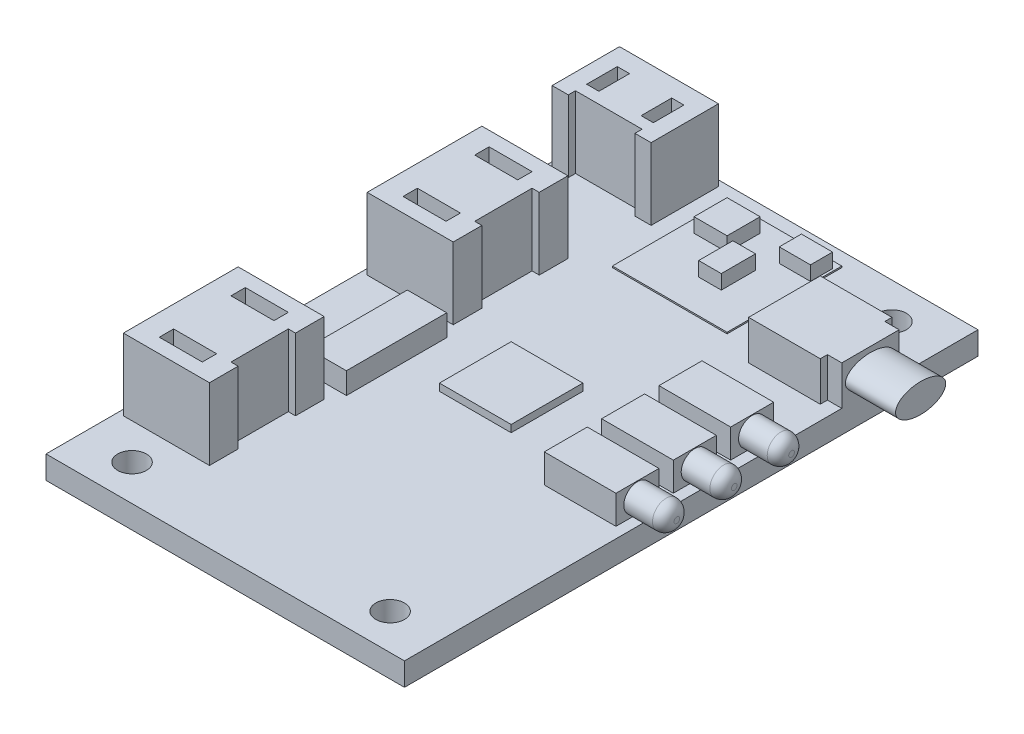
SolidWorks part; units mm, degrees
ref_plane "Front Plane" through (0, 0, 0) normal (0, 0, 1) x (1, 0, 0)
ref_plane "Top Plane" through (0, 0, 0) normal (0, 1, 0) x (1, 0, 0)
ref_plane "Right Plane" through (0, 0, 0) normal (1, 0, 0) x (0, 0, -1)
sketch "Sketch1" plane through (0, 0, 0) normal (0, 1, 0) x (1, 0, 0)
  line L1 (0, 0) -> (25, 0)
  line L2 (0, 0) -> (0, 40)
  line L3 (0, 40) -> (25, 40)
  line L4 (25, 0) -> (25, 40)
  dimension "D1" = 40
  dimension "D2" = 25
extrude "Boss-Extrude1" add sketch "Sketch1" along normal blind 1.6 contours L2 L3 L4 L1
sketch "Sketch2" plane through (0, 1.6, 0) normal (0, 1, 0) x (1, 0, 0)
  line L1 (14.9411, 22.5) -> (9.9411, 22.5)
  line L2 (14.9411, 22.5) -> (14.9411, 17.5)
  line L3 (14.9411, 17.5) -> (9.9411, 17.5)
  line L4 (9.9411, 22.5) -> (9.9411, 17.5)
  line L5 (14.9411, 22.5) -> (9.9411, 17.5) construction
  line L6 (14.9411, 17.5) -> (9.9411, 22.5) construction
  point P0 (12.4411, 20)
  point P5 (12.5, 19.8855)
  point P6 (12.4411, 20.1289)
  dimension "D1" = 5
  dimension "D2" = 20
extrude "Boss-Extrude2" add sketch "Sketch2" along normal blind 0.5
sketch "Sketch3" plane through (0, 1.6, 0) normal (0, 1, 0) x (1, 0, 0)
  line L0 (0, 0) -> (25, 0) construction
  line L1 (19.25, 18.5) -> (24.25, 18.5)
  line L2 (19.25, 18.5) -> (19.25, 15.5)
  line L3 (19.25, 15.5) -> (24.25, 15.5)
  line L4 (24.25, 18.5) -> (24.25, 15.5)
  line L5 (19.25, 18.5) -> (24.25, 15.5) construction
  line L6 (19.25, 15.5) -> (24.25, 18.5) construction
  line L7 (25, 0) -> (25, 40) construction
  point P0 (21.75, 17)
  point P5 (21.4832, 17.3272)
  dimension "D1" = 15.5
  dimension "D2" = 3
  dimension "D3" = 5
  dimension "D4" = 0.75
extrude "Boss-Extrude3" add sketch "Sketch3" along normal blind 2
sketch "Sketch4" plane through (24.25, 0, 0) normal (1, 0, 0) x (0, 0, -1)
  line L6 (18.5, 3.6) -> (18.5, 1.6) construction
  line L8 (15.5, 3.6) -> (18.5, 3.6) construction
  circle A0 centre (17, 2.6) radius 0.95
  point P2 (0, 0)
  point P7 (18.5, 2.6)
  point P10 (17, 3.6)
  dimension "D1" = 1.9
extrude "Boss-Extrude6" add sketch "Sketch4" along normal blind 2.75
fillet "Fillet2" radius 0.75 1 edges at (27, 2.6, -17.95)
pattern_linear "LPattern2" count 3 spacing 4 along (0, 0, -1) of "Boss-Extrude3", "Boss-Extrude6", "Fillet2"
sketch "Sketch5" plane through (0, 1.6, 0) normal (0, 1, 0) x (1, 0, 0)
  line L0 (24, 30.5) -> (24, 30)
  line L1 (24, 35) -> (19, 35)
  line L2 (24, 35) -> (24, 34.5)
  line L3 (24, 30) -> (19, 30)
  line L4 (19, 35) -> (19, 30)
  line L5 (24, 35) -> (19, 30) construction
  line L6 (24, 30) -> (19, 35) construction
  line L7 (25, 0) -> (25, 40) construction
  line L8 (0, 40) -> (25, 40) construction
  line L9 (25, 34.5) -> (24, 34.5)
  line L14 (25, 34.5) -> (25, 30.5)
  line L15 (25, 30.5) -> (24, 30.5)
  point P0 (21.5, 32.5)
  point P9 (21.5, 32.5)
  point P14 (25, 32.5)
  dimension "D1" = 1
  dimension "D2" = 5
  dimension "D3" = 5
  dimension "D4" = 4
extrude "Boss-Extrude7" add sketch "Sketch5" along normal blind 2.75
sketch "Sketch6" plane through (25, 0, 0) normal (1, 0, 0) x (0, 0, -1)
  line L0 (30.5, 4.35) -> (34.5, 4.35) construction
  line L1 (35, 4.35) -> (35, 1.6) construction
  ellipse E0 centre (32.5, 2.975) end of major axis (30.75, 2.975) minor radius 1
  point P1 (0, 0)
  point P2 (34.1034, 2.9375)
  point P5 (32.5, 4.35)
  point P13 (35, 2.975)
  point P14 (0, 0)
  point P15 (32.5, 2.2386)
  dimension "D1" = 3.5
  dimension "D2" = 2
extrude "Boss-Extrude8" add sketch "Sketch6" along normal blind 3.5
sketch "Sketch7" plane through (0, 1.6, 0) normal (0, 1, 0) x (1, 0, 0)
  line L0 (0, 40) -> (25, 40) construction
  line L1 (16.5, 39) -> (8.5, 39)
  line L2 (16.5, 39) -> (16.5, 31)
  line L3 (16.5, 31) -> (8.5, 31)
  line L4 (8.5, 39) -> (8.5, 31)
  line L5 (16.5, 39) -> (8.5, 31) construction
  line L6 (16.5, 31) -> (8.5, 39) construction
  line L8 (16.3371, 38.5219) -> (14.1621, 38.5219)
  line L9 (16.3371, 38.5219) -> (16.3371, 36.9773)
  line L10 (16.3371, 36.9773) -> (14.1621, 36.9773)
  line L11 (14.1621, 38.5219) -> (14.1621, 36.9773)
  line L12 (16.3371, 38.5219) -> (14.1621, 36.9773) construction
  line L13 (16.3371, 36.9773) -> (14.1621, 38.5219) construction
  line L14 (11.6751, 35.8249) -> (9.3704, 35.8249)
  line L15 (11.6751, 35.8249) -> (11.6751, 38.1296)
  line L16 (11.6751, 38.1296) -> (9.3704, 38.1296)
  line L17 (9.3704, 35.8249) -> (9.3704, 38.1296)
  line L18 (11.6751, 35.8249) -> (9.3704, 38.1296) construction
  line L19 (11.6751, 38.1296) -> (9.3704, 35.8249) construction
  line L20 (12.1773, 35.7271) -> (13.7546, 35.7271)
  line L21 (12.1773, 35.7271) -> (12.1773, 33.341)
  line L22 (12.1773, 33.341) -> (13.7546, 33.341)
  line L23 (13.7546, 35.7271) -> (13.7546, 33.341)
  line L24 (12.1773, 35.7271) -> (13.7546, 33.341) construction
  line L25 (12.1773, 33.341) -> (13.7546, 35.7271) construction
  point P0 (12.5, 35)
  point P5 (10.5227, 36.9773)
  point P8 (12.5, 40)
  point P9 (15.2496, 37.7496)
  point P18 (12.966, 34.534)
  dimension "D1" = 1
  dimension "D2" = 8
extrude "Boss-Extrude9" add sketch "Sketch7" along normal blind 0.1 contours L1 L4 L3 L2 L11 L8 L9 L10 L14 L17 L16 L15 L20 L23 L22 L21 | L8 L11 L10 L9 | L17 L14 L15 L16 | L23 L20 L21 L22
sketch "Sketch8" plane through (0, 1.7, 0) normal (0, 1, 0) x (1, 0, 0)
  line L0 (11.6751, 35.8249) -> (9.3704, 35.8249) construction
  line L1 (9.3704, 35.8249) -> (9.3704, 38.1296) construction
  line L2 (11.6751, 38.1296) -> (9.3704, 38.1296) construction
  line L3 (11.6751, 35.8249) -> (11.6751, 38.1296) construction
  line L4 (13.7546, 35.7271) -> (13.7546, 33.341) construction
  line L5 (12.1773, 33.341) -> (13.7546, 33.341) construction
  line L6 (12.1773, 35.7271) -> (12.1773, 33.341) construction
  line L7 (12.1773, 35.7271) -> (13.7546, 35.7271) construction
  line L8 (16.3371, 38.5219) -> (16.3371, 36.9773) construction
  line L9 (16.3371, 36.9773) -> (14.1621, 36.9773) construction
  line L10 (14.1621, 38.5219) -> (14.1621, 36.9773) construction
  line L11 (16.3371, 38.5219) -> (14.1621, 38.5219) construction
  line L12 (11.6751, 35.8249) -> (9.3704, 35.8249)
  line L13 (9.3704, 35.8249) -> (9.3704, 38.1296)
  line L14 (11.6751, 38.1296) -> (9.3704, 38.1296)
  line L15 (11.6751, 35.8249) -> (11.6751, 38.1296)
  line L16 (13.7546, 35.7271) -> (13.7546, 33.341)
  line L17 (12.1773, 33.341) -> (13.7546, 33.341)
  line L18 (12.1773, 35.7271) -> (12.1773, 33.341)
  line L19 (12.1773, 35.7271) -> (13.7546, 35.7271)
  line L20 (16.3371, 38.5219) -> (16.3371, 36.9773)
  line L21 (16.3371, 36.9773) -> (14.1621, 36.9773)
  line L22 (14.1621, 38.5219) -> (14.1621, 36.9773)
  line L23 (16.3371, 38.5219) -> (14.1621, 38.5219)
extrude "Boss-Extrude10" add sketch "Sketch8" along normal blind 1
sketch "Sketch9" plane through (0, 1.6, 0) normal (0, 1, 0) x (1, 0, 0)
  line L1 (6.95, 21) -> (4.2, 21)
  line L2 (6.95, 21) -> (6.95, 14)
  line L3 (6.95, 14) -> (4.2, 14)
  line L4 (4.2, 21) -> (4.2, 14)
  line L5 (6.95, 21) -> (4.2, 14) construction
  line L6 (6.95, 14) -> (4.2, 21) construction
  line L7 (0, 0) -> (0, 40) construction
  line L9 (9.9411, 17.5) -> (14.9411, 17.5) construction
  point P0 (5.575, 17.5)
  point P5 (0, 0)
  point P11 (0, 0)
  point P12 (0, 0)
  point P15 (5.575, 18.4772)
  point P16 (12.4411, 17.5)
  dimension "D1" = 7
  dimension "D2" = 4.2
  dimension "D3" = 2.75
extrude "Boss-Extrude11" add sketch "Sketch9" along normal blind 1.5
sketch "Sketch10" plane through (0, 1.6, 0) normal (0, 1, 0) x (1, 0, 0)
  line L1 (6.4, 13) -> (0.4, 13)
  line L2 (6.4, 13) -> (6.4, 11)
  line L3 (6.4, 5) -> (0.4, 5)
  line L4 (0.4, 13) -> (0.4, 5)
  line L5 (6.4, 13) -> (0.4, 5) construction
  line L6 (6.4, 5) -> (0.4, 13) construction
  line L10 (0, 0) -> (25, 0) construction
  line L11 (0, 0) -> (0, 40) construction
  line L12 (6.4, 9) -> (3.4, 9) construction
  line L13 (4.9, 11) -> (1.9, 11)
  line L14 (4.9, 6) -> (1.9, 6)
  line L15 (4.9, 6) -> (4.9, 7)
  line L16 (4.9, 7) -> (1.9, 7)
  line L17 (1.9, 6) -> (1.9, 7)
  line L18 (4.9, 6) -> (1.9, 7) construction
  line L19 (4.9, 7) -> (1.9, 6) construction
  line L20 (1.9, 12) -> (1.9, 11)
  line L21 (4.9, 12) -> (1.9, 12)
  line L22 (4.9, 12) -> (4.9, 11)
  line L23 (6.4, 7) -> (6.4, 5)
  line L24 (6.4, 7) -> (5.9, 7)
  line L26 (6.4, 11) -> (5.9, 11)
  line L27 (5.9, 7) -> (5.9, 11)
  point P0 (3.4, 9)
  point P7 (3.4, 6.5)
  dimension "D1" = 8
  dimension "D2" = 5
  dimension "D3" = 0.4
  dimension "D4" = 6
  dimension "D5" = 2
  dimension "D6" = 1
  dimension "D7" = 0.5
extrude "Boss-Extrude12" add sketch "Sketch10" along normal blind 5
pattern_linear "LPattern3" count 2 spacing 17 along (0, 0, -1) of "Boss-Extrude12"
sketch "Sketch11" plane through (0, 1.6, 0) normal (0, 1, 0) x (1, 0, 0)
  line L0 (0, 40) -> (25, 40) construction
  line L1 (7.3, 39.6) -> (0.4, 39.6)
  line L2 (7.3, 39.6) -> (7.3, 34.9)
  line L3 (7.3, 34.9) -> (6.175, 34.9)
  line L4 (0.4, 39.6) -> (0.4, 34.9)
  line L5 (0, 0) -> (0, 40) construction
  line L6 (3.85, 39.6) -> (3.85, 35.4) construction
  line L7 (5.3209, 36.1828) -> (6.175, 36.1828)
  line L8 (2.3791, 38.3172) -> (1.525, 38.3172)
  line L9 (2.3791, 38.3172) -> (2.3791, 36.1828)
  line L10 (2.3791, 36.1828) -> (1.525, 36.1828)
  line L11 (1.525, 38.3172) -> (1.525, 36.1828)
  line L12 (2.3791, 38.3172) -> (1.525, 36.1828) construction
  line L13 (2.3791, 36.1828) -> (1.525, 38.3172) construction
  line L14 (6.175, 38.3172) -> (6.175, 36.1828)
  line L15 (5.3209, 38.3172) -> (6.175, 38.3172)
  line L16 (5.3209, 38.3172) -> (5.3209, 36.1828)
  line L17 (6.175, 34.9) -> (6.175, 35.4)
  line L19 (1.525, 34.9) -> (1.525, 35.4)
  line L20 (1.525, 35.4) -> (6.175, 35.4)
  line L22 (1.525, 34.9) -> (0.4, 34.9)
  point P10 (1.9521, 37.25)
  dimension "D1" = 0.4
  dimension "D2" = 0.4
  dimension "D3" = 4.7
  dimension "D4" = 6.9
  dimension "D5" = 0.5
extrude "Boss-Extrude13" add sketch "Sketch11" along normal blind 5
sketch "Sketch12" plane through (0, 1.6, 0) normal (0, 1, 0) x (1, 0, 0)
  line L0 (0, 0) -> (0, 40) construction
  line L1 (0, 0) -> (25, 0) construction
  line L2 (12.5, 0) -> (12.5, 40) construction
  line L3 (0, 40) -> (25, 40) construction
  line L4 (0, 20) -> (25, 20) construction
  line L5 (25, 0) -> (25, 30.5) construction
  circle A0 centre (3.5, 2.5) radius 1
  circle A1 centre (21.5, 2.5) radius 1
  circle A2 centre (21.5, 37.5) radius 1
  dimension "D1" = 2
  dimension "D2" = 3.5
  dimension "D3" = 2.5
sketch "Sketch13" plane through (0, 1.6, 0) normal (0, 1, 0) x (1, 0, 0)
  line L0 (0, 20) -> (25, 20) construction
  line L1 (0, 0) -> (0, 40) construction
  line L2 (25, 0) -> (25, 30.5) construction
extrude "Cut-Extrude1" cut sketch "Sketch12" against normal up to next
